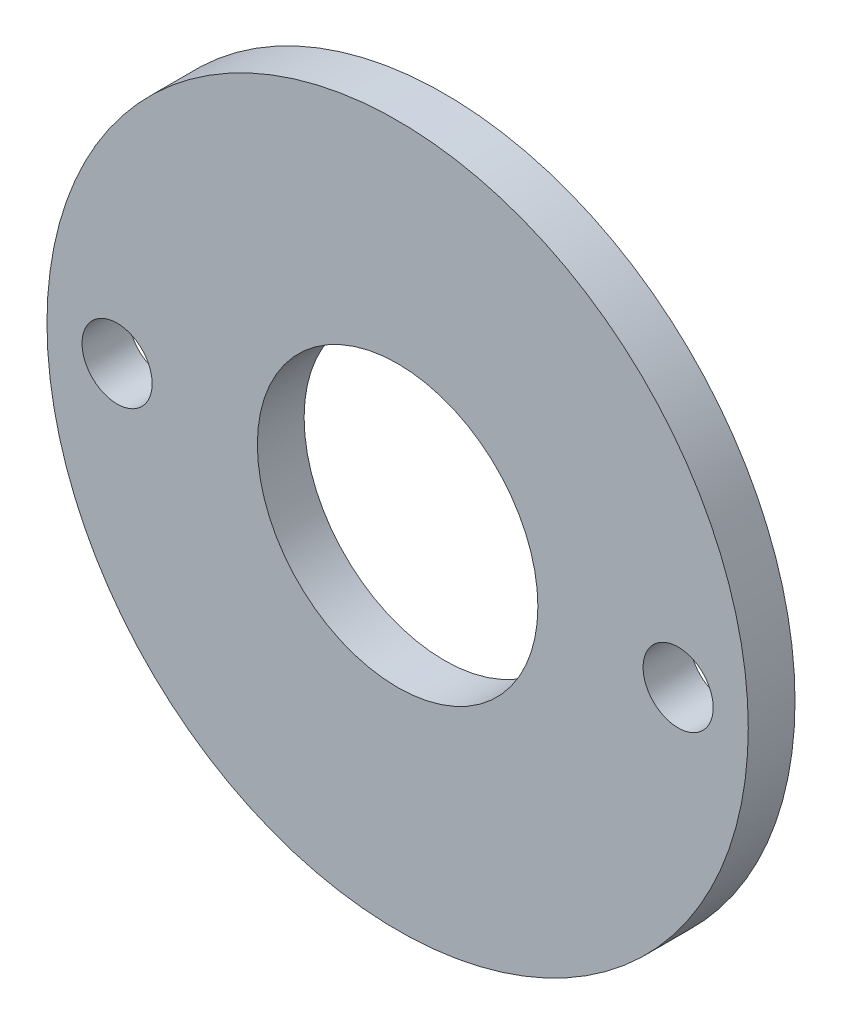
SolidWorks part; units mm, degrees
ref_plane "Front Plane" through (0, 0, 0) normal (0, 0, 1) x (1, 0, 0)
ref_plane "Top Plane" through (0, 0, 0) normal (0, 1, 0) x (1, 0, 0)
ref_plane "Right Plane" through (0, 0, 0) normal (1, 0, 0) x (0, 0, -1)
sketch "Sketch1" plane through (0, 0, 0) normal (0, 0, 1) x (1, 0, 0)
  line L0 (-12, 0) -> (0, 0) construction
  line L1 (0, 0) -> (12, 0) construction
  circle A0 centre (0, 0) radius 9.5 construction
  circle A1 centre (0, 0) radius 6
  circle A2 centre (0, 0) radius 15
  circle A3 centre (12, 0) radius 1.5
  circle A4 centre (-12, 0) radius 1.5
  dimension "D1" = 12
  dimension "D2" = 19
  dimension "D4" = 30
  dimension "D5" = 3
  dimension "D6" = 3
  dimension "D3" = 12
extrude "Boss-Extrude1" add sketch "Sketch1" along normal blind 2
